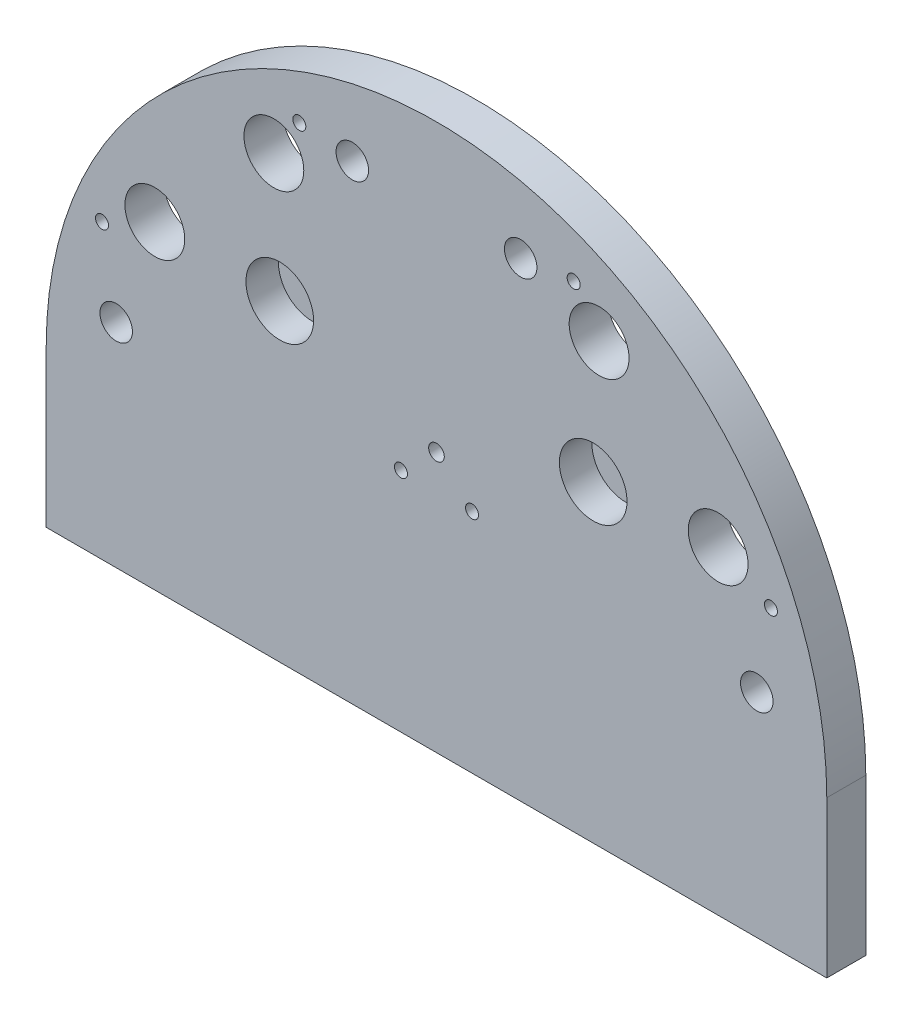
SolidWorks part; units mm, degrees
ref_plane "前视基准面" through (0, 0, 0) normal (0, 0, 1) x (1, 0, 0)
ref_plane "上视基准面" through (0, 0, 0) normal (0, 1, 0) x (1, 0, 0)
ref_plane "右视基准面" through (0, 0, 0) normal (1, 0, 0) x (0, 0, -1)
sketch "草图1" plane through (0, 0, 0) normal (0, 0, 1) x (1, 0, 0)
  line L0 (0, 0) -> (-125, 216.5064)
  line L1 (0, 0) -> (-216.5064, 125)
  line L2 (0, 0) -> (0, 120.7678)
  line L3 (0, 0) -> (-295.4423, -52.0945)
  line L4 (0, 0) -> (-181.7099, 0)
  line L5 (0, 0) -> (295.4423, -52.0945)
  arc A0 (295.4423, -52.0945) -> (-295.4423, -52.0945) centre (0, 0) ccw
  arc A1 (246.2019, -43.412) -> (-246.2019, -43.412) centre (0, 0) ccw construction
  circle A2 centre (-125, 216.5064) radius 23
  circle A3 centre (-216.5064, 125) radius 23
  circle A4 centre (216.5064, 125) radius 23
  circle A5 centre (125, 216.5064) radius 23
  dimension "D1" = 600
  dimension "D2" = 500
  dimension "D3" = 46
  dimension "D4" = 46
  dimension "D5" = 30
  dimension "D6" = 30
  dimension "D7" = 10
extrude "凸台-拉伸1" add sketch "草图1" along normal blind 30
sketch "草图2" plane through (0, 0, 30) normal (0, 0, 1) x (1, 0, 0)
  line L0 (0, 0) -> (-250, 0)
  line L1 (0, 0) -> (250, 0)
  arc A0 (-250, 0) -> (250, 0) centre (0, 0) ccw
  dimension "D1" = 500
extrude "切除-拉伸1" cut sketch "草图2" against normal blind 50
sketch "草图10" plane through (0, 0, 30) normal (0, 0, 1) x (1, 0, 0)
  line L0 (0, 0) -> (0, 87.7305) construction
  line L1 (0, 0) -> (-72.3497, 0) construction
  line L2 (250, 0) -> (-250, 0) construction
  line L3 (0, 0) -> (-246.2019, 43.412) construction
  line L4 (0, 0) -> (-64.7048, 241.4815) construction
  circle A0 centre (0, 0) radius 250 construction
  circle A1 centre (-246.2019, 43.412) radius 12.5
  circle A2 centre (246.2019, 43.412) radius 12.5
  circle A3 centre (-64.7048, 241.4815) radius 12.5
  circle A4 centre (64.7048, 241.4815) radius 12.5
  dimension "D1" = 500
  dimension "D2" = 25
  dimension "D5" = 25
  dimension "D3" = 10
  dimension "D4" = 15
extrude "切除-拉伸6" cut sketch "草图10" against normal through all
sketch "草图15" plane through (0, 0, 30) normal (0, 0, 1) x (1, 0, 0)
  line L0 (0, 0) -> (0, 105.5492) construction
  line L1 (250, 0) -> (-250, 0) construction
  circle A0 centre (-257.0813, 104.8727) radius 5
  circle A1 centre (-105.4431, 246.4861) radius 5
  circle A2 centre (-27.3267, 54.2719) radius 5
  circle A3 centre (27.3267, 54.2719) radius 5
  circle A4 centre (105.4431, 246.4861) radius 5
  circle A5 centre (257.0813, 104.8727) radius 5
extrude "切除-拉伸8" cut sketch "草图15" against normal through all
sketch "草图16" plane through (0, 0, 30) normal (0, 0, 1) x (1, 0, 0)
  line L0 (-300, 0) -> (-300, -120)
  line L1 (-300, -120) -> (300, -120)
  line L2 (300, -120) -> (300, 0)
  line L4 (250, 0) -> (-250, 0) construction
  line L5 (-300, 0) -> (300, 0)
  arc A0 (295.4423, -52.0945) -> (-295.4423, -52.0945) centre (0, 0) ccw construction
  dimension "D1" = 120
extrude "凸台-拉伸2" add sketch "草图16" against normal up to surface (30 mm away) up to face at (-252.0813, 104.8727, 0)
sketch "草图17" plane through (0, 0, 30) normal (0, 0, 1) x (1, 0, 0)
  line L0 (0, 0) -> (0, 124.8814) construction
  circle A0 centre (-120.47, 120.47) radius 26
  circle A1 centre (120.47, 120.47) radius 26
  dimension "D1" = 52
  dimension "D3" = 120.47
  dimension "D2" = 120.47
extrude "切除-拉伸9" cut sketch "草图17" against normal up to next
sketch "草图18" plane through (0, 0, 0) normal (0, 0, -1) x (-1, 0, 0)
  circle A0 centre (120.47, 120.47) radius 26
  circle A1 centre (-120.47, 120.47) radius 26
extrude "凸台-拉伸3" add sketch "草图18" against normal blind 5
sketch "草图19" plane through (0, 0, 0) normal (0, 0, -1) x (-1, 0, 0)
  line L0 (-300, -120) -> (300, -120) construction
  circle A0 centre (0, 80) radius 6
  point P4 (0, 0)
  dimension "D1" = 200
  dimension "D2" = 12
extrude "切除-拉伸10" cut sketch "草图19" against normal blind 58
